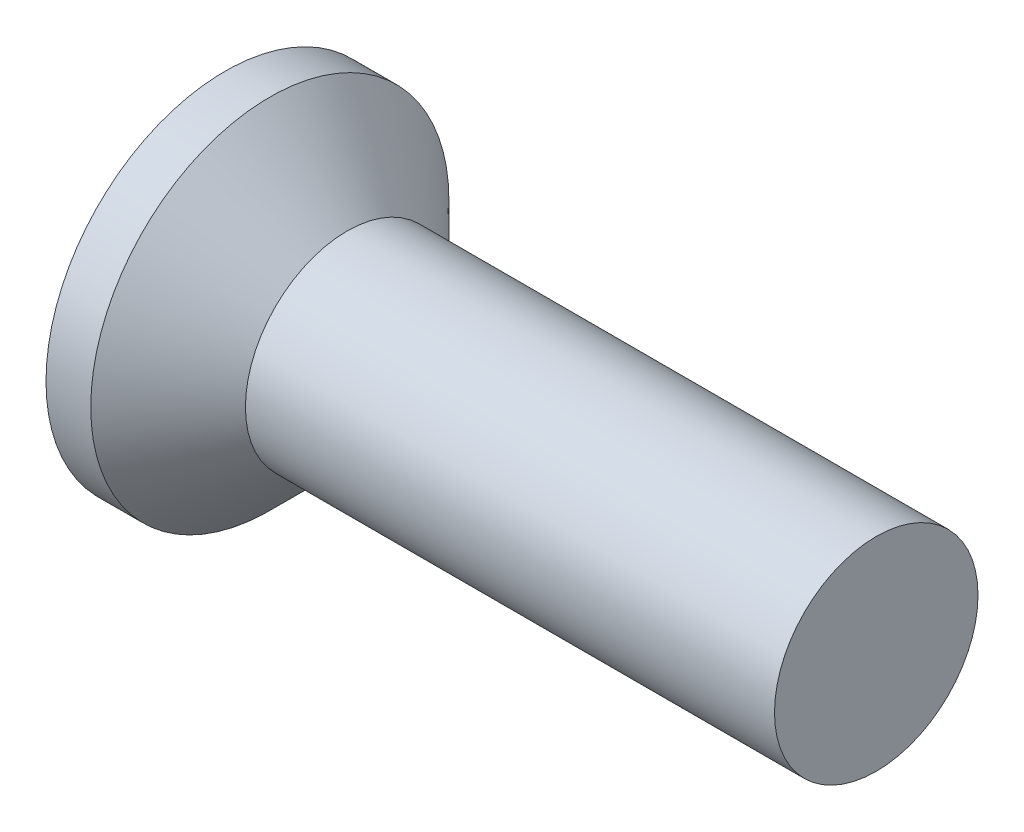
SolidWorks part; units mm, degrees
ref_plane "Front" through (0, 0, 0) normal (0, 0, 1) x (1, 0, 0)
ref_plane "Top" through (0, 0, 0) normal (0, 1, 0) x (1, 0, 0)
ref_plane "Right" through (0, 0, 0) normal (1, 0, 0) x (0, 0, -1)
sketch "Sketch1" plane through (0, 0, 0) normal (0, 0, 1) x (1, 0, 0)
  line L0 (8, 1.25) -> (2.4, 1.25)
  line L1 (2.4, 1.25) -> (1.5, 1.25)
  line L2 (1.5, 1.25) -> (0.55, 2.2)
  line L3 (0.55, 2.2) -> (0, 2.2)
  line L4 (8, 1.25) -> (8, 0)
  line L5 (4.5158, 0) -> (-89.8219, 0) construction
  line L6 (8, 0) -> (0, 0)
  line L7 (0, 2.2) -> (0, 0)
  dimension "D1" = 45
  dimension "d" = 2.5
  dimension "dk" = 4.4
  dimension "l" = 8
  dimension "k" = 1.5
  dimension "a" = 0.9
revolve "Base" add sketch "Sketch1" angle 360 about L5
cosmetic thread "ThreadCosmetic1" [suppressed] parameters "bb"=6.5, "THD_MINOR"=2.013
sketch "Sketch6" plane through (0, 0, 0) normal (1, 0, 0) x (0, 0, -1)
  line L0 (-1.9271, 0) -> (2.0512, 0) construction
  line L1 (0, 1.8651) -> (0, -2.0207) construction
  line L2 (0.29, 0.29) -> (0.29, 1.45)
  line L3 (0.29, 1.45) -> (-0.29, 1.45)
  line L4 (-0.29, 0.29) -> (-0.29, 1.45)
  line L5 (0.29, 0.29) -> (1.45, 0.29)
  line L6 (1.45, 0.29) -> (1.45, -0.29)
  line L7 (-1.45, 0.29) -> (-1.45, -0.29)
  line L8 (-0.29, 0.29) -> (-1.45, 0.29)
  line L9 (-0.29, -0.29) -> (-1.45, -0.29)
  line L10 (0.29, -0.29) -> (1.45, -0.29)
  line L11 (-0.29, -0.29) -> (-0.29, -1.45)
  line L12 (0.29, -1.45) -> (-0.29, -1.45)
  line L13 (0.29, -0.29) -> (0.29, -1.45)
  point P16 (-1.45, 0)
  point P17 (1.45, 0)
  dimension "D1" = 0.58
  dimension "m" = 2.9
extrude "CrossRecess" cut sketch "Sketch6" along normal blind 0.75
draft "Draft9" type of draft neutral plane draft angle 30 faces to draft 4 face at (0.375, 1.45, 0) face at (0.375, 0, 1.45) face at (0.375, -1.45, 0) face at (0.375, 0, -1.45) neutral plane through (0, 2.2, 0) neutral plane normal (-1, 0, 0) parameters "D1"=30
fillet "Fillet5" radius 0.3 4 edges at (0.375, -0.29, -0.29) (0.375, 0.29, -0.29) (0.375, 0.29, 0.29) (0.375, -0.29, 0.29)
sketch "Sketch7" plane through (0, 0, 0) normal (1, 0, 0) x (0, 0, -1)
  line L0 (-2.0126, 0) -> (1.9757, 0) construction
  line L1 (0, 1.9314) -> (0, -2.0126) construction
  line L2 (0, 0) -> (1.5555, 1.5555) construction
  line L3 (0, 0.4333) -> (1.0253, 1.0253)
  line L4 (-1.5402, 1.5402) -> (0, 0) construction
  line L5 (0.4333, 0) -> (1.0253, 1.0253)
  line L6 (0, -0.4333) -> (1.0253, -1.0253)
  line L7 (0.4333, 0) -> (1.0253, -1.0253)
  line L8 (-0.4333, 0) -> (-1.0253, -1.0253)
  line L9 (0, -0.4333) -> (-1.0253, -1.0253)
  line L10 (-0.4333, 0) -> (-1.0253, 1.0253)
  line L11 (0, 0.4333) -> (-1.0253, 1.0253)
  dimension "D3" = 15
extrude "Cut-Extrude3" [suppressed] cut sketch "Sketch7" along normal blind 10 draft 20
sketch "Sketch8" plane through (0, 0, 0) normal (0, 0, 1) x (1, 0, 0)
  line L0 (-17, 1.4935) -> (-18.1, 1.25)
  line L1 (-18.1, 1.25) -> (1.5, 1.25)
  line L3 (8, -1.25) -> (8, 1.25) construction
  line L6 (1.5, 1.25) -> (1.5, 6.25)
  line L7 (1.5, 6.25) -> (-17, 6.25)
  line L8 (-17, 6.25) -> (-17, 1.4935)
  line L9 (62.4753, 0.2435) -> (52.9594, 0.2435) construction
  dimension "D1" = 5
  dimension "x" = 1.1
  dimension "b" = 25
sketch "Sketch9" plane through (0, 0, 0) normal (0, 0, 1) x (1, 0, 0)
  line L0 (8, 1.0391) -> (8.1218, 1.25)
  line L1 (8.1218, 1.25) -> (8.1218, 1.4935)
  line L2 (8.1218, 1.4935) -> (7.8782, 1.4935)
  line L3 (7.8782, 1.4935) -> (7.8782, 1.25)
  line L4 (7.8782, 1.25) -> (8, 1.0391)
  line L5 (0, 0) -> (73.843, 0) construction
  line L6 (8, -1.25) -> (8, 1.25) construction
  dimension "D1" = 2.5
  dimension "D2" = 0.2435
revolve "Cut-Revolve10" [suppressed] cut sketch "Sketch9" angle 360 about L5
pattern_linear "LPattern10" [suppressed] count 22 spacing 0.2922 along (1, 0, 0)
equation "\"D1@Sketch6\" = \"m@Sketch6\" / 5"
equation "\"D1@CrossRecess\" = \"k@Sketch1\" / 2"
equation "\"D1@Sketch9\" = \"d@Sketch1\""
equation "\"D2@Sketch9\" =  ( \"d@Sketch1\" - \"THD_MINOR@ThreadCosmetic1\" )  / 2"
equation "\"D3@LPattern10\" = \"D2@Sketch9\" * 1.2"
equation "\"D1@LPattern10\" = \"bb@ThreadCosmetic1\" / \"D3@LPattern10\" "
